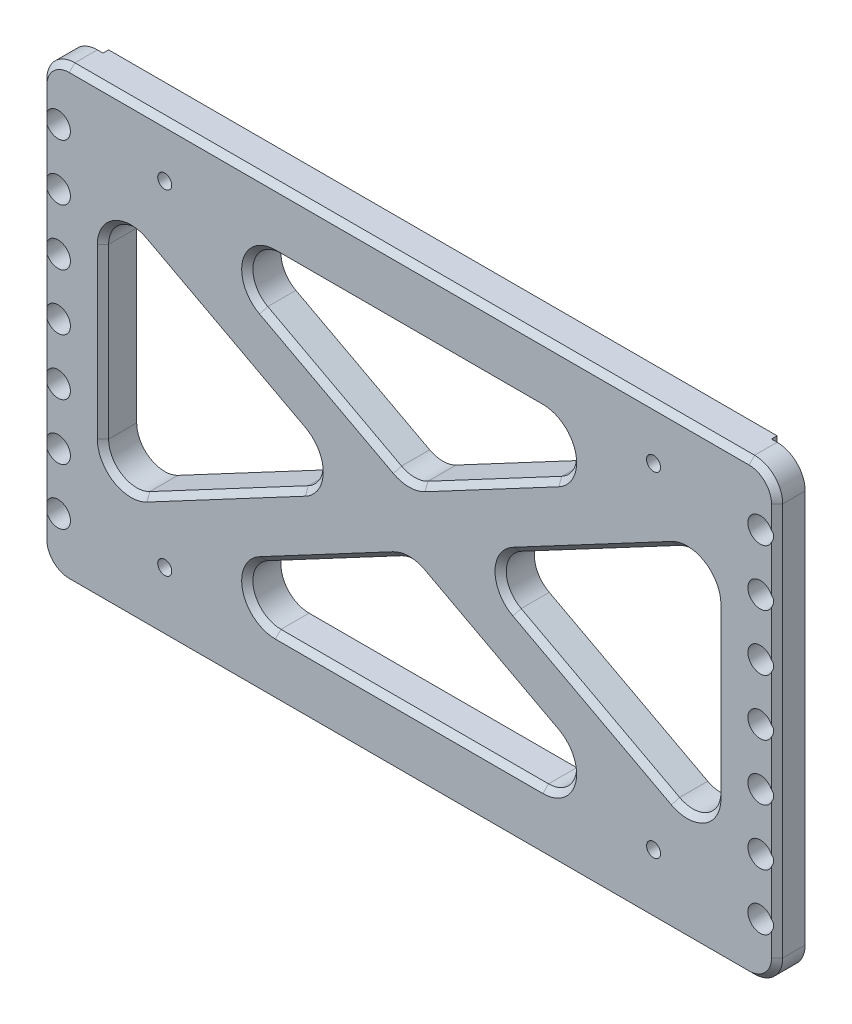
SolidWorks part; units mm, degrees
material "7075-T6 (SN)"
ref_plane "前视基准面" through (0, 0, 0) normal (0, 0, 1) x (1, 0, 0)
ref_plane "上视基准面" through (0, 0, 0) normal (0, 1, 0) x (1, 0, 0)
ref_plane "右视基准面" through (0, 0, 0) normal (1, 0, 0) x (0, 0, -1)
sketch "草图3" plane through (0, 0, 0) normal (0, 0, 1) x (1, 0, 0)
  line L0 (-57.5, -11.5) -> (57.5, -11.5) construction
  line L1 (-65.5, -11.5) -> (65.5, -11.5)
  line L2 (-65.5, -91.5) -> (65.5, -91.5)
  line L3 (65.5, -5.5) -> (65.5, -101.8916) construction
  line L4 (-65.5, -101.8916) -> (-65.5, -5.5) construction
  line L5 (65.5, -11.5) -> (65.5, -91.5)
  line L6 (-65.5, -91.5) -> (-65.5, -11.5)
  line L7 (-57.5, -11.5) -> (57.5, -11.5) construction
  line L8 (-57.5, -91.5) -> (57.5, -91.5) construction
  dimension "D1" = 80
extrude "凸台-拉伸3" add sketch "草图3" along normal blind 5
sketch "草图4" plane through (0, 0, 5) normal (0, 0, 1) x (1, 0, 0)
  line L0 (-65.5, -91.5) -> (65.5, -91.5) construction
  line L1 (59.5, -91.5) -> (-59.5, -91.5)
  line L2 (59.5, -91.5) -> (59.5, -11.5)
  line L3 (59.5, -11.5) -> (-59.5, -11.5)
  line L4 (-59.5, -91.5) -> (-59.5, -11.5)
  line L5 (59.5, -11.5) -> (59.5, -101.8916) construction
  line L6 (60.5, -11.5) -> (-60.5, -11.5) construction
  line L7 (65.5, -11.5) -> (-65.5, -11.5) construction
extrude "凸台-拉伸4" add sketch "草图4" against normal blind 6
fillet "圆角2" radius 5 4 edges at (65.5, -11.5, 2.5) (-65.5, -11.5, 2.5) (-65.5, -91.5, 2.5) (65.5, -91.5, 2.5)
chamfer "倒角1" distance 1 angle 45 8 edges at (-65.5, -51.5, 5) (-64.0355, -90.0355, 5) (-64.0355, -12.9645, 5) (0, -91.5, 5) (0, -11.5, 5) (64.0355, -90.0355, 5) (64.0355, -12.9645, 5) (65.5, -51.5, 5)
sketch "草图5" plane through (0, 0, 5) normal (0, 0, 1) x (1, 0, 0)
  line L4 (-54.5, -22.5) -> (54.5, -80.5)
  line L5 (-54.5, -80.5) -> (54.5, -22.5)
  line L6 (-52.1513, -84.914) -> (56.8487, -26.914)
  line L7 (-56.8487, -26.914) -> (52.1513, -84.914)
  line L8 (-54.5, -22.5) -> (-54.5, -80.5)
  line L9 (-54.5, -80.5) -> (54.5, -80.5)
  line L10 (54.5, -80.5) -> (54.5, -22.5)
  line L11 (54.5, -22.5) -> (-54.5, -22.5)
  line L12 (-54.5, -22.5) -> (-54.5, -80.5)
  line L13 (-54.5, -80.5) -> (54.5, -80.5)
  line L14 (54.5, -80.5) -> (54.5, -22.5)
  line L15 (54.5, -22.5) -> (-54.5, -22.5)
  line L16 (-56.8487, -76.086) -> (52.1513, -18.086)
  line L17 (-52.1513, -18.086) -> (56.8487, -76.086)
  dimension "D2" = 5
  dimension "D1" = 10
  dimension "D3" = 5
extrude "切除-拉伸1" cut sketch "草图5" against normal blind 6 contours L12 L16 L7 | L15 L17 L16 | L6 L17 L14 | L6 L13 L7
fillet "圆角3" radius 5 12 edges at (54.5, -28.1638, 2) (54.5, -74.8362, 2) (10.644, -51.5, 2) (0, -45.8362, 2) (-43.856, -22.5, 2) (43.856, -22.5, 2) (-10.644, -51.5, 2) (-54.5, -74.8362, 2) (-54.5, -28.1638, 2) (0, -57.1638, 2) (43.856, -80.5, 2) (-43.856, -80.5, 2)
chamfer "倒角2" distance 1 angle 45 24 edges at (-52.0745, -70.7981, 5) (-54.5, -51.5, 5) (-33.0453, -63.4199, 5) (-52.0745, -32.2019, 5) (-16.288, -51.5, 5) (-33.0453, -39.5801, 5) (28.6667, -26.2896, 5) (0, -22.5, 5) (14.2564, -38.2502, 5) (-28.6667, -26.2896, 5) (0, -45.1724, 5) (-14.2564, -38.2502, 5) (52.0745, -32.2019, 5) (33.0453, -39.5801, 5) (54.5, -51.5, 5) (16.288, -51.5, 5) (52.0745, -70.7981, 5) (33.0453, -63.4199, 5) (-28.6667, -76.7104, 5) (-14.2564, -64.7498, 5) (0, -80.5, 5) (0, -57.8276, 5) (28.6667, -76.7104, 5) (14.2564, -64.7498, 5)
sketch "草图6" plane through (0, 0, 5) normal (0, 0, 1) x (1, 0, 0)
  line L0 (65.5, -51.5) -> (59.5, -51.5) construction
  line L1 (65.5, -16.5) -> (65.5, -86.5) construction
  line L2 (62.5, -41.5) -> (62.5, -61.5) construction
  line L3 (62.5, -31.5) -> (62.5, -71.5) construction
  line L4 (62.5, -21.5) -> (62.5, -81.5) construction
  circle A0 centre (62.5, -21.5) radius 2.2
  circle A1 centre (62.5, -31.5) radius 2.2
  circle A2 centre (62.5, -41.5) radius 2.2
  circle A3 centre (62.5, -51.5) radius 2.2
  circle A4 centre (62.5, -61.5) radius 2.2
  circle A5 centre (62.5, -71.5) radius 2.2
  circle A6 centre (62.5, -81.5) radius 2.2
  point P7 (62.5, -51.5)
  point P11 (62.5, -51.5)
  point P14 (62.5, -51.5)
  dimension "D1" = 7
extrude "切除-拉伸2" cut sketch "草图6" against normal blind 11
mirror "镜向1" about plane through (0, 0, 0) normal (1, 0, 0) of "切除-拉伸2"
sketch "草图7" plane through (0, 0, 5) normal (0, 0, 1) x (1, 0, 0)
  line L0 (0, -90.5) -> (0, -50.52) construction
  line L1 (-60.5, -90.5) -> (60.5, -90.5) construction
  line L3 (-43.51, -80.29) -> (43.51, -80.29)
  line L4 (-43.51, -80.29) -> (-43.51, -20.75)
  line L5 (-43.51, -20.75) -> (43.51, -20.75)
  line L6 (43.51, -80.29) -> (43.51, -20.75)
  line L7 (-43.51, -80.29) -> (43.51, -20.75) construction
  line L8 (-43.51, -20.75) -> (43.51, -80.29) construction
hole_wizard "M3 螺纹孔1" positions "草图8" profile "草图9" tap size "M3" standard "GB"
sketch "草图8" plane through (0, 0, 5) normal (0, 0, 1) x (1, 0, 0)
  point P0 (-43.51, -20.75)
  point P3 (43.51, -20.75)
  point P6 (43.51, -80.29)
  point P9 (-43.51, -80.29)
sketch "草图9" plane through (-43.51, -20.75, 5) normal (1, 0, 0) x (0, -1, 0)
  line L0 (0, 0) -> (0, 8.2511)
  line L1 (0, 8.2511) -> (1.25, 7.5)
  line L2 (1.25, 7.5) -> (1.25, 0)
  line L5 (1.25, 0) -> (0, 0)
  line L10 (0, 8.2511) -> (-1.25, 7.5) construction
  line L11 (0, -6.35) -> (0, 107.95) construction
  dimension "螺纹孔钻头直径" = 2.5
  dimension "螺纹孔钻头深度" = 7.5
  dimension "导头角度" = 118
cosmetic thread "孔螺蚊线1" parameters "D1"=6, "D2"=3
cosmetic thread "孔螺蚊线2" parameters "D1"=6, "D2"=3
cosmetic thread "孔螺蚊线3" parameters "D1"=6, "D2"=3
cosmetic thread "孔螺蚊线4" parameters "D1"=6, "D2"=3
